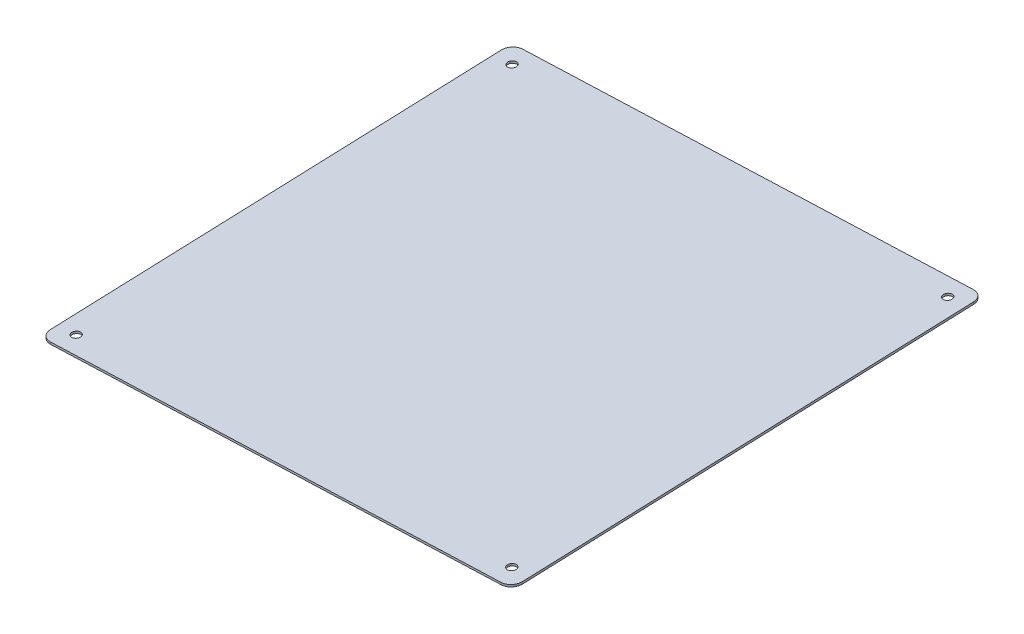
SolidWorks part; units mm, degrees
ref_plane "Front Plane" through (0, 0, 0) normal (0, 0, 1) x (1, 0, 0)
ref_plane "Top Plane" through (0, 0, 0) normal (0, 1, 0) x (1, 0, 0)
ref_plane "Right Plane" through (0, 0, 0) normal (1, 0, 0) x (0, 0, -1)
sketch "Sketch2" plane through (75.2093, -1945.5005, -70.5625) normal (-0.0386, 0.9986, 0.0362) x (0.9993, 0.0386, 0.0007)
  line L7 (-488.8604, 45.6874) -> (-68.8604, 45.6874)
  line L8 (-498.8604, 55.6874) -> (-498.8604, 475.6874)
  line L9 (-488.8604, 485.6874) -> (-68.8604, 485.6874)
  line L10 (-58.8604, 55.6874) -> (-58.8604, 475.6874)
  line L11 (-498.8604, 45.6874) -> (-58.8604, 485.6874) construction
  line L12 (-498.8604, 485.6874) -> (-58.8604, 45.6874) construction
  arc A3 (-68.8604, 45.6874) -> (-58.8604, 55.6874) centre (-68.8604, 55.6874) ccw
  arc A4 (-488.8604, 45.6874) -> (-498.8604, 55.6874) centre (-488.8604, 55.6874) cw
  arc A5 (-68.8604, 485.6874) -> (-58.8604, 475.6874) centre (-68.8604, 475.6874) cw
  arc A6 (-498.8604, 475.6874) -> (-488.8604, 485.6874) centre (-488.8604, 475.6874) cw
  point P0 (-278.8604, 265.6874)
  dimension "D1" = 440
  dimension "D2" = 10
extrude "Boss-Extrude1" add sketch "Sketch2" along normal blind 2 contours A4 L8 A6 L9 A5 L10 A3 L7
ref_plane "Plane1" through (-0.1859, 9.6229, -265.513) normal (0.0007, -0.0362, 0.9993) x (1, 0, -0.0007)
ref_plane "Plane2" through (-278.6525, -10.7651, -0.1951) normal (-0.9993, -0.0386, -0.0007) x (-0.0007, 0, 1)
extrude "Cut-Extrude1" cut sketch "Sketch3" along normal blind 150
sketch "Sketch3" plane through (-103.2872, -1885.7611, -334.1344) normal (0.0386, -0.9986, -0.0362) x (-0.0007, 0.0362, -0.9993)
  circle A0 centre (-203.0711, 100.3522) radius 4.1
mirror "Mirror1" about plane through (-278.6525, -10.7651, -0.1951) normal (-0.9993, -0.0386, -0.0007) of "Cut-Extrude1"
mirror "Mirror2" about plane through (-0.1859, 9.6229, -265.513) normal (0.0007, -0.0362, 0.9993) of "Mirror1", "Cut-Extrude1"
